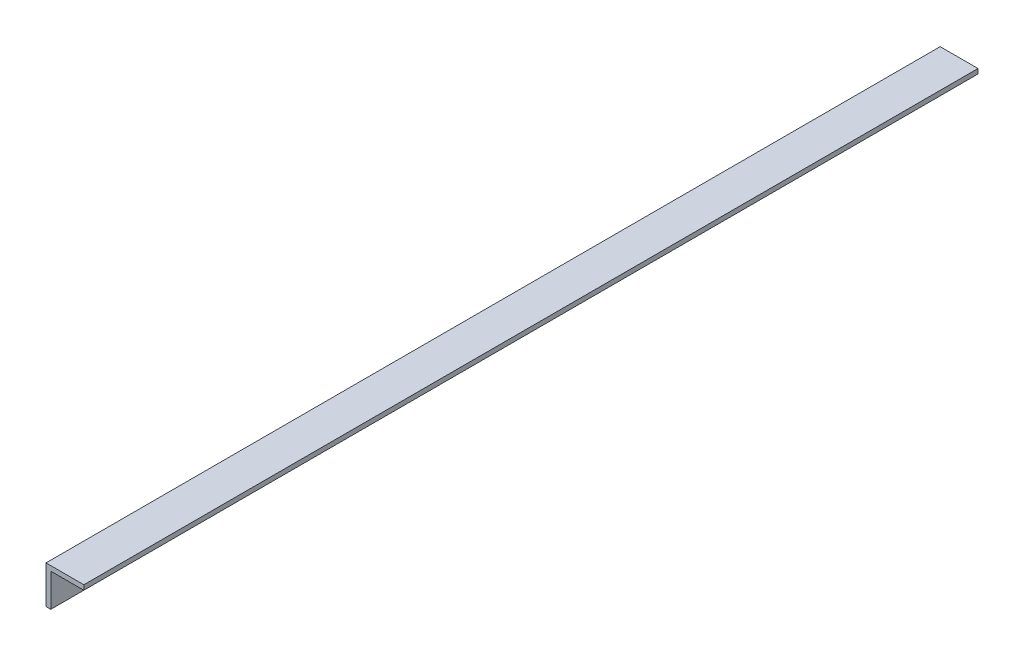
SolidWorks part; units mm, degrees
ref_plane "Front Plane" through (0, 0, 0) normal (0, 0, 1) x (1, 0, 0)
ref_plane "Top Plane" through (0, 0, 0) normal (0, 1, 0) x (1, 0, 0)
ref_plane "Right Plane" through (0, 0, 0) normal (1, 0, 0) x (0, 0, -1)
sketch "Sketch1" plane through (0, 0, 0) normal (0, 0, 1) x (1, 0, 0)
  line L0 (-13.4471, 11.2806) -> (-0.7471, 11.2806)
  line L1 (-0.7471, 11.2806) -> (-0.7471, 9.6806)
  line L2 (-0.7471, 9.6806) -> (-11.8471, 9.6806)
  line L3 (-11.8471, 9.6806) -> (-11.8471, -1.4194)
  line L4 (-11.8471, -1.4194) -> (-13.4471, -1.4194)
  line L5 (-13.4471, -1.4194) -> (-13.4471, 11.2806)
  dimension "D1" = 12.7
  dimension "D2" = 12.7
  dimension "D3" = 1.6
  dimension "D4" = 1.6
extrude "Boss-Extrude1" add sketch "Sketch1" along normal blind 300
